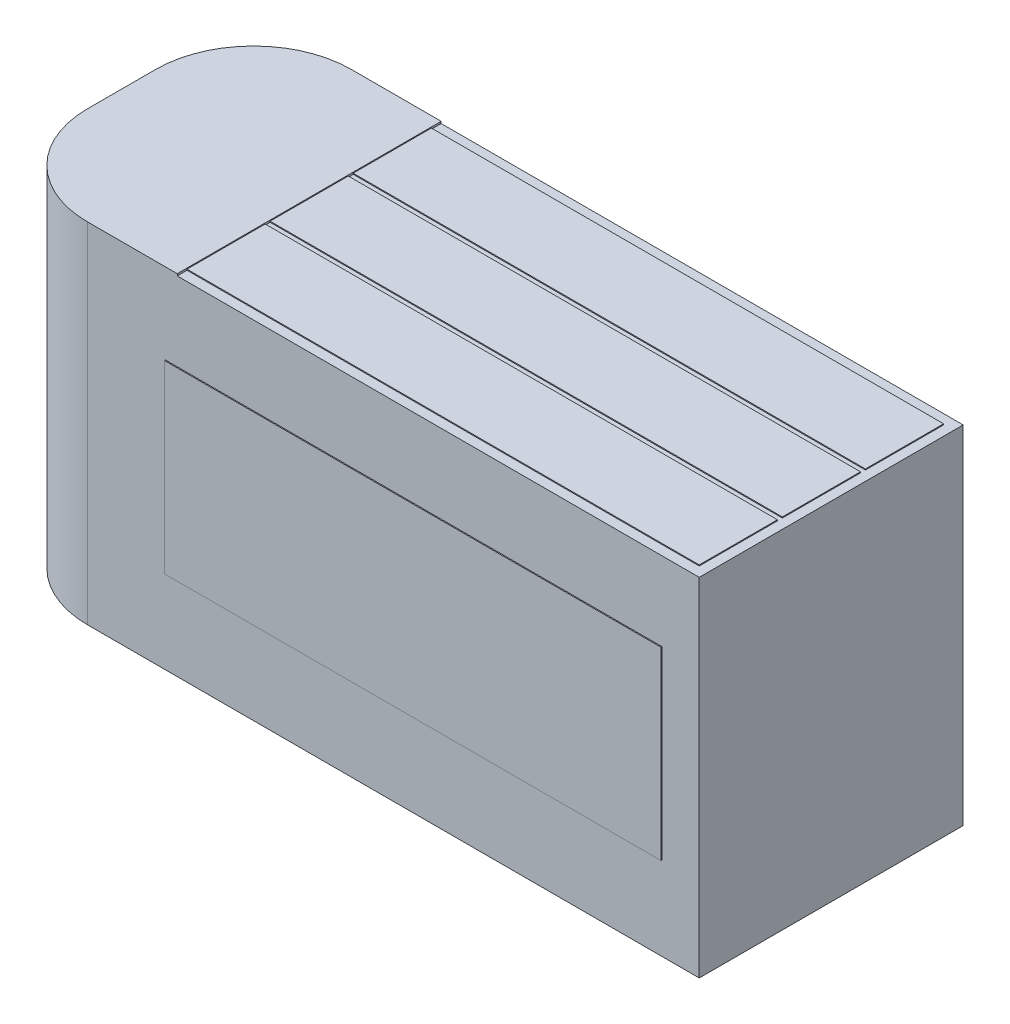
SolidWorks part; units mm, degrees
ref_plane "Front Plane" through (0, 0, 0) normal (0, 0, 1) x (1, 0, 0)
ref_plane "Top Plane" through (0, 0, 0) normal (0, 1, 0) x (1, 0, 0)
ref_plane "Right Plane" through (0, 0, 0) normal (1, 0, 0) x (0, 0, -1)
sketch "Sketch1" plane through (0, 0, 0) normal (0, 0, 1) x (1, 0, 0)
  line L1 (-36.3, -17.75) -> (36.3, -17.75)
  line L2 (-36.3, -17.75) -> (-36.3, 17.75)
  line L3 (-36.3, 17.75) -> (36.3, 17.75)
  line L4 (36.3, -17.75) -> (36.3, 17.75)
  line L5 (-36.3, -17.75) -> (36.3, 17.75) construction
  line L6 (-36.3, 17.75) -> (36.3, -17.75) construction
  point P0 (0, 0)
  dimension "D1" = 72.6
  dimension "D2" = 35.5
extrude "Boss-Extrude1" add sketch "Sketch1" along normal blind 27
fillet "Fillet1" radius 10 2 edges at (-36.3, 0, 0) (-36.3, 0, 27)
sketch "Sketch2" plane through (0, 17.75, 0) normal (0, 1, 0) x (1, 0, 0)
  line L0 (35.3, -22) -> (36.3, -22) construction
  line L1 (35.3, -1) -> (-17.1, -1)
  line L2 (35.3, -1) -> (35.3, -9)
  line L3 (35.3, -9) -> (-17.1, -9)
  line L4 (-17.1, -1) -> (-17.1, -9)
  line L5 (35.3, -9.5) -> (-17.1, -9.5)
  line L6 (35.3, -9.5) -> (35.3, -17.5)
  line L7 (35.3, -17.5) -> (-17.1, -17.5)
  line L8 (-17.1, -9.5) -> (-17.1, -17.5)
  line L9 (-17.1, -18) -> (35.3, -18)
  line L10 (-17.1, -18) -> (-17.1, -26)
  line L11 (-17.1, -26) -> (35.3, -26)
  line L12 (35.3, -18) -> (35.3, -26)
  line L13 (36.3, -27) -> (36.3, 0) construction
  line L14 (35.3, -13.5) -> (36.3, -13.5) construction
  line L15 (35.3, -5) -> (36.3, -5) construction
  line L16 (36.3, -5) -> (36.3, -13.5) construction
  line L17 (36.3, -13.5) -> (36.3, -22) construction
  line L18 (9.1, -9.5) -> (9.1, -9) construction
  line L19 (9.1, -17.5) -> (9.1, -18) construction
  line L20 (9.1, -1) -> (9.1, 0) construction
  line L21 (36.3, 0) -> (-26.3, 0) construction
  line L22 (9.1, -26) -> (9.1, -27) construction
  line L23 (36.3, -27) -> (-26.3, -27) construction
  dimension "D1" = 0.5
  dimension "D2" = 1
  dimension "D3" = 1
extrude "Boss-Extrude2" add sketch "Sketch2" along normal blind 0.1
sketch "Sketch3" plane through (0, 0, 27) normal (0, 0, 1) x (1, 0, 0)
  line L1 (-18.3, 9.7) -> (32.5, 9.7)
  line L2 (-18.3, 9.7) -> (-18.3, -9.2)
  line L3 (-18.3, -9.2) -> (32.5, -9.2)
  line L4 (32.5, 9.7) -> (32.5, -9.2)
extrude "Boss-Extrude3" add sketch "Sketch3" along normal blind 0.1
sketch "Sketch4" plane through (0, 17.75, 0) normal (0, 1, 0) x (1, 0, 0)
  line L1 (-26.3, 0) -> (-17.1, 0)
  line L2 (-17.1, 0) -> (-17.1, -27)
  line L3 (-17.1, -27) -> (-26.3, -27)
  line L4 (36.3, 0) -> (-26.3, 0) construction
  line L5 (36.3, -27) -> (-26.3, -27) construction
  line L6 (-36.3, -10) -> (-36.3, -17)
  arc A0 (-26.3, -27) -> (-36.3, -17) centre (-26.3, -17) cw
  arc A1 (-26.3, 0) -> (-36.3, -10) centre (-26.3, -10) ccw
extrude "Boss-Extrude4" add sketch "Sketch4" along normal blind 0.2
sketch "Sketch5" plane through (0, 0, 0) normal (0, 0, -1) x (-1, 0, 0)
  line L1 (-33.2747, 11.3) -> (20.2253, 11.3)
  line L2 (-33.2747, 11.3) -> (-33.2747, -8.4)
  line L3 (-33.2747, -8.4) -> (20.2253, -8.4)
  line L4 (20.2253, 11.3) -> (20.2253, -8.4)
extrude "Boss-Extrude5" add sketch "Sketch5" along normal blind 0.1
